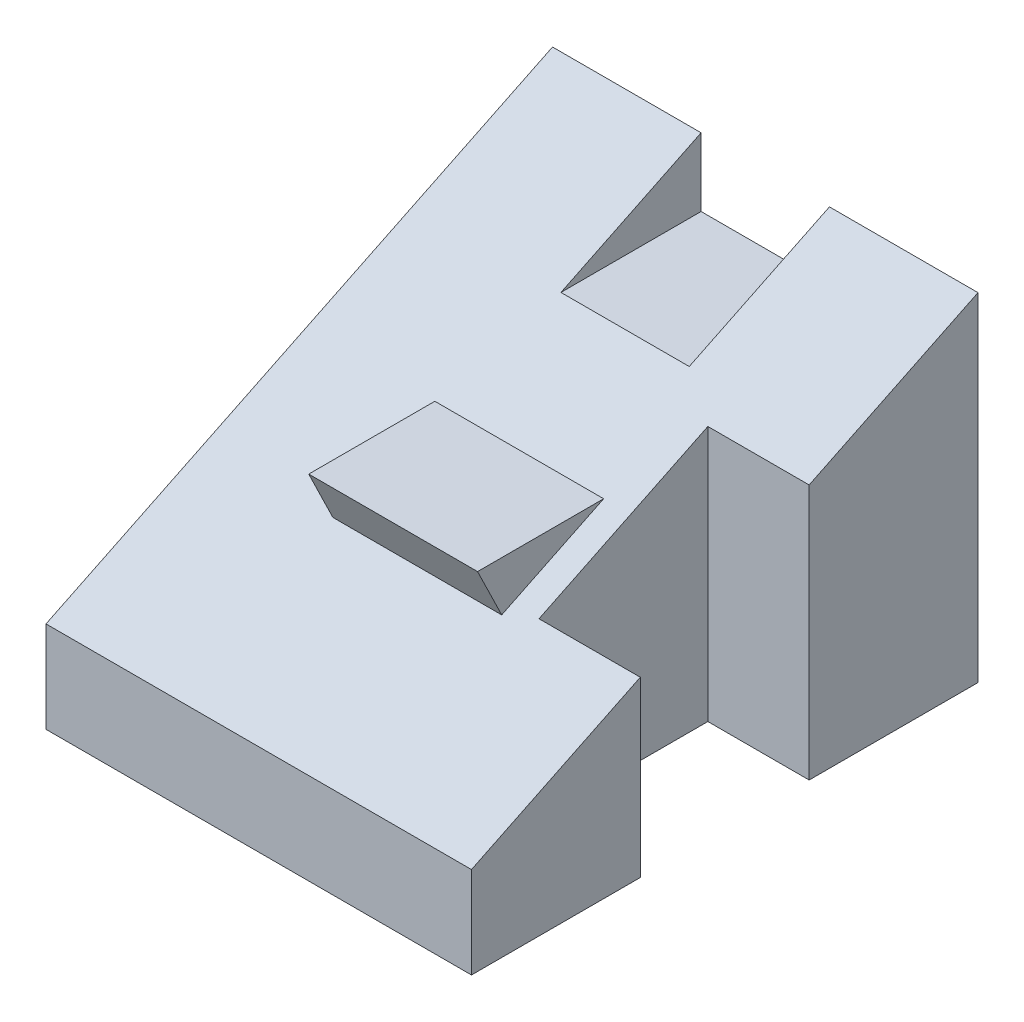
SolidWorks part; units mm, degrees
ref_plane "Front Plane" through (0, 0, 0) normal (0, 0, 1) x (1, 0, 0)
ref_plane "Top Plane" through (0, 0, 0) normal (0, 1, 0) x (1, 0, 0)
ref_plane "Right Plane" through (0, 0, 0) normal (1, 0, 0) x (0, 0, -1)
sketch "Sketch1" plane through (0, 0, 0) normal (0, 1, 0) x (1, 0, 0)
  line L0 (0, 0) -> (63, 0)
  line L1 (63, 0) -> (63, 25)
  line L2 (63, 25) -> (48, 25)
  line L3 (48, 25) -> (48, 50)
  line L4 (48, 50) -> (63, 50)
  line L5 (63, 50) -> (63, 75)
  line L6 (63, 75) -> (0, 75)
  line L7 (0, 75) -> (0, 0)
  point P4 (-88.5213, 52.0633)
  point P10 (-68.4997, 73.9533)
  dimension "D1" = 63
  dimension "D2" = 15
  dimension "D3" = 25
  dimension "D4" = 25
  dimension "D5" = 25
  dimension "D7" = 75
extrude "Boss-Extrude2" add sketch "Sketch1" along normal blind 50
sketch "Sketch3" plane through (63, 0, 0) normal (1, 0, 0) x (0, 0, -1)
  line L0 (75, 50) -> (0, 13.5232)
  line L1 (0, 50) -> (0, 0) construction
  line L2 (0, 13.5232) -> (0, 50)
  line L3 (0, 50) -> (75, 50)
extrude "Cut-Extrude2" cut sketch "Sketch3" against normal blind 63
sketch "Sketch4" plane through (0, 10.9362, 5.3189) normal (0, 0.8993, 0.4374) x (1, 0, 0)
  line L0 (63, 89.3147) -> (41, 89.3147)
  line L1 (63, 89.3147) -> (0, 89.3147) construction
  line L2 (0, 89.3147) -> (22, 89.3147)
  line L3 (41, 89.3147) -> (41, 66.234)
  line L4 (41, 66.234) -> (22, 66.234)
  line L5 (22, 66.234) -> (22, 89.3147)
  line L6 (0, 89.3147) -> (0, 66.234)
  line L7 (0, 5.9147) -> (0, 89.3147) construction
  line L8 (0, 66.234) -> (22, 66.234)
  line L9 (41, 66.234) -> (63, 66.234)
  line L10 (63, 61.5147) -> (63, 89.3147) construction
  line L11 (63, 66.234) -> (63, 89.3147)
  dimension "D1" = 22
  dimension "D2" = 22
sketch "Sketch6" plane through (0, 10.9362, 5.3189) normal (0, 0.8993, 0.4374) x (1, 0, 0)
  line L0 (0, 48.8082) -> (19, 48.8082)
  line L1 (0, 5.9147) -> (0, 89.3147) construction
  line L2 (19, 48.8082) -> (44, 48.8082)
  line L3 (44, 48.8082) -> (44, 32.0177)
  line L4 (44, 32.0177) -> (19, 32.0177)
  line L5 (19, 32.0177) -> (19, 48.8082)
  dimension "D1" = 19
  dimension "D2" = 25
extrude "Boss-Extrude4" add sketch "Sketch6" along normal blind 16 contours L5 L4 L3 L2
sketch "Sketch10" plane through (44, 0, 0) normal (1, 0, 0) x (0, 0, -1)
  line L0 (38.5734, 32.2836) -> (19.9023, 32.2836)
  line L1 (16.476, 39.3284) -> (23.4739, 24.9399) construction
  line L4 (19.9023, 32.2836) -> (16.476, 39.3284)
  line L5 (16.476, 39.3284) -> (31.5754, 46.6721)
  line L6 (31.5754, 46.6721) -> (38.5734, 32.2836)
  point P5 (27.4962, 21.9603)
extrude "Cut-Extrude8" cut sketch "Sketch10" against normal blind 25
sketch "Sketch11" plane through (0, 0, -75) normal (0, 0, -1) x (-1, 0, 0)
  line L0 (-63, 39.9052) -> (-41, 39.9052)
  line L1 (-22, 39.9052) -> (0, 39.9052)
  line L2 (0, 39.9052) -> (0, 50)
  line L3 (0, 50) -> (-22, 50)
  line L4 (-22, 50) -> (-22, 39.9052)
  line L5 (-41, 50) -> (-63, 50)
  line L6 (-63, 50) -> (-63, 39.9052)
  line L7 (-41, 50) -> (-41, 39.9052)
  line L8 (-41, 39.9052) -> (-22, 39.9052)
  line M7 (0, 50) -> (-63, 50)
extrude "Cut-Extrude9" cut sketch "Sketch11" against normal blind 25 contours L7 L8 L4 M7
